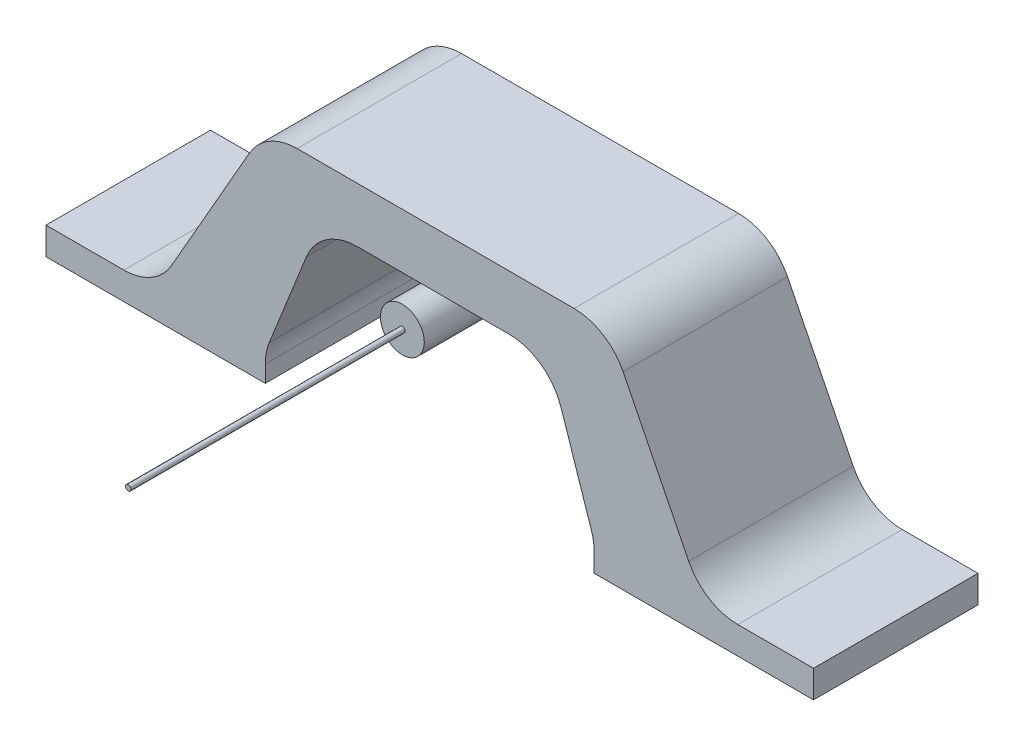
SolidWorks part; units mm, degrees
ref_plane "Płaszczyzna przednia" through (0, 0, 0) normal (0, 0, 1) x (1, 0, 0)
ref_plane "Płaszczyzna górna" through (0, 0, 0) normal (0, 1, 0) x (1, 0, 0)
ref_plane "Płaszczyzna prawa" through (0, 0, 0) normal (1, 0, 0) x (0, 0, -1)
sketch "Szkic1" plane through (0, 0, 0) normal (0, 0, 1) x (1, 0, 0)
  line L1 (-30, 0) -> (-70, 0)
  line L2 (-30, 0) -> (-30, 5)
  line L3 (-30, 5) -> (-70, 5)
  line L4 (-70, 0) -> (-70, 5)
  line L5 (30, 0) -> (70, 0)
  line L6 (30, 0) -> (30, 5)
  line L7 (30, 5) -> (70, 5)
  line L8 (70, 0) -> (70, 5)
  point P8 (0, 0)
  point P9 (0, 0)
  point P10 (0, 0)
  point P11 (0, 0)
  point P12 (0, 0)
  point P13 (0, 0)
  point P14 (0, 0)
extrude "Dodanie-wyciągnięcie1" add sketch "Szkic1" along normal blind 30
sketch "Szkic2" plane through (0, 0, 0) normal (0, 0, 1) x (1, 0, 0)
  line L0 (-30, 5) -> (-20, 30)
  line L1 (-20, 30) -> (21.6667, 30)
  line L2 (21.6667, 30) -> (30, 5)
  line L3 (30, 5) -> (50, 5)
  line L4 (70, 5) -> (30, 5) construction
  line L5 (50, 5) -> (32.5, 40)
  line L6 (32.5, 40) -> (-30, 40)
  line L7 (-30, 40) -> (-50, 5)
  line L8 (-30, 5) -> (-70, 5) construction
  line L9 (-50, 5) -> (-30, 5)
  point P11 (0, 0)
  point P15 (0, 0)
  point P16 (0, 0)
  point P17 (0, 0)
  point P18 (0, 0)
  point P19 (0, 0)
  point P20 (0, 0)
  point P21 (0, 0)
  point P22 (0, 0)
  point P23 (0, 0)
  point P24 (0, 0)
  point P25 (0, 0)
  point P26 (0, 0)
  point P27 (0, 0)
  point P28 (0, 0)
extrude "Dodanie-wyciągnięcie2" add sketch "Szkic2" along normal blind 30
fillet "Zaokrąglenie1" radius 10 8 edges at (-30, 5, 15) (30, 5, 15) (21.6667, 30, 15) (-20, 30, 15) (-30, 40, 15) (32.5, 40, 15) (50, 5, 15) (-50, 5, 15)
sketch "Szkic3" plane through (0, 0, 0) normal (0, 0, 1) x (1, 0, 0)
  circle A0 centre (0, 26) radius 4
  point P2 (0, 0)
  point P3 (0, 0)
  point P4 (0, 0)
  dimension "D1" = 8
extrude "Dodanie-wyciągnięcie3" add sketch "Szkic3" along normal blind 35 separate body contours A0
sketch "Szkic4" plane through (0, 0, 35) normal (0, 0, 1) x (1, 0, 0)
  circle A0 centre (0, 26) radius 0.5
extrude "Dodanie-wyciągnięcie4" add sketch "Szkic4" along normal blind 50
